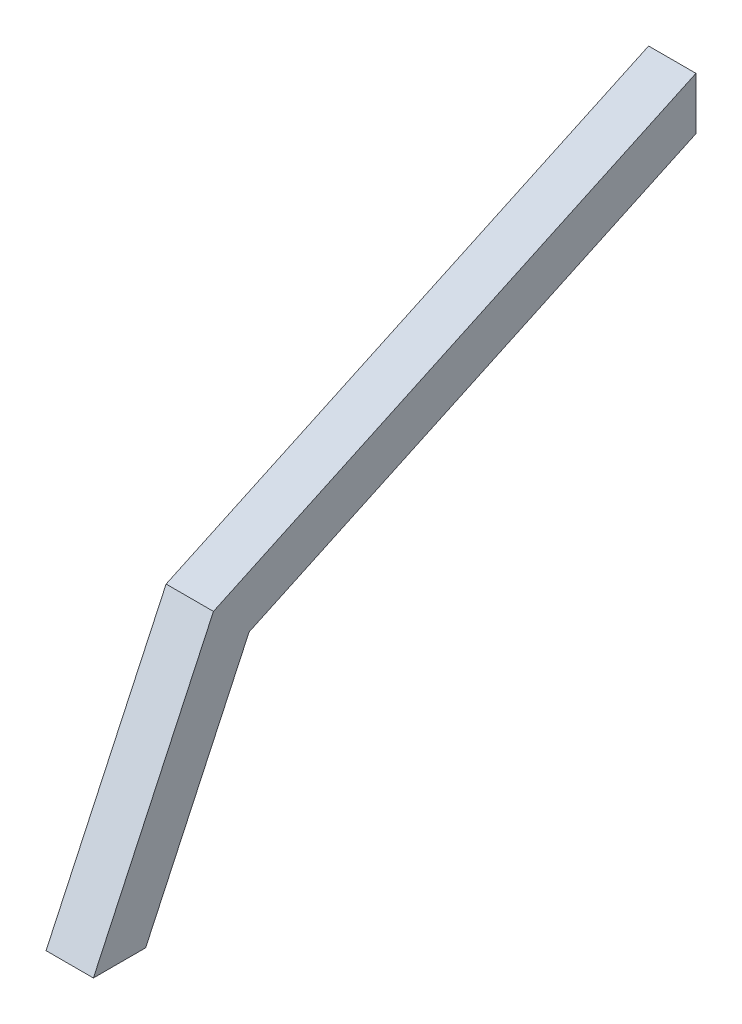
SolidWorks part; units mm, degrees
material "ASTM A36 Steel"
ref_plane "Front Plane" through (0, 0, 0) normal (0, 0, 1) x (1, 0, 0)
ref_plane "Top Plane" through (0, 0, 0) normal (0, 1, 0) x (1, 0, 0)
ref_plane "Right Plane" through (0, 0, 0) normal (1, 0, 0) x (0, 0, -1)
sketch "Sketch1" plane through (0, 0, 0) normal (1, 0, 0) x (0, 0, -1)
  line L0 (0, 0) -> (-100, 0) construction
  line L1 (-100, 0) -> (-19.7852, 46.3121) construction
  dimension "D1" = 30
  dimension "D2" = 100
sketch "Sketch2" plane through (0, 0, 0) normal (1, 0, 0) x (0, 0, -1)
  line L17 (0, 0) -> (-22.0676, 0)
  line L28 (-22.0676, 0) -> (28.6466, 108.7569)
  line L29 (0, 0) -> (232.4632, 181.6201) construction
  line L34 (28.6466, 108.7569) -> (232.4632, 203.6829)
  line L35 (0, 0) -> (43.6942, 93.7024)
  line L36 (43.6942, 93.7024) -> (232.4632, 181.6201)
  line L37 (232.4632, 181.6201) -> (232.4632, 203.6829)
  point P10 (335.1967, 43.9665)
  point P14 (333.8719, 43.9665)
  dimension "D1" = 38
  dimension "D2" = 20
  dimension "D3" = 20
  dimension "D4" = 120
  dimension "D5" = 65
  dimension "D7" = 295
extrude "Boss-Extrude1" add sketch "Sketch2" along normal blind 20
shell "Shell1" thickness 1.2
